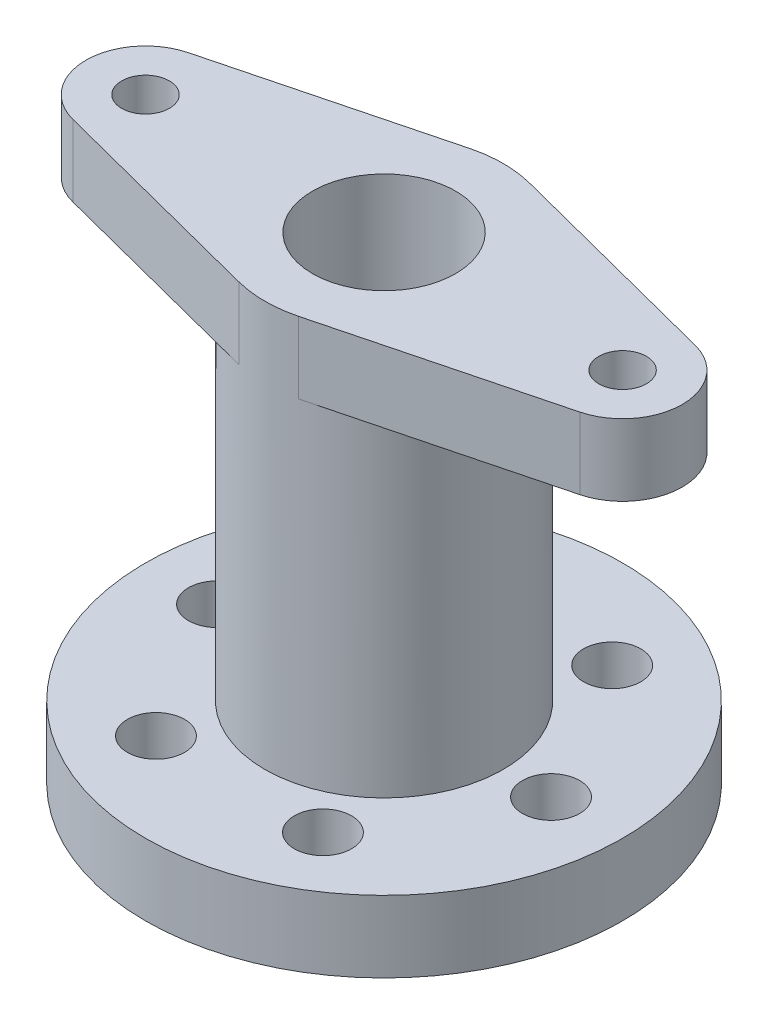
SolidWorks part; units mm, degrees
ref_plane "Front Plane" through (0, 0, 0) normal (0, 0, 1) x (1, 0, 0)
ref_plane "Top Plane" through (0, 0, 0) normal (0, 1, 0) x (1, 0, 0)
ref_plane "Right Plane" through (0, 0, 0) normal (1, 0, 0) x (0, 0, -1)
sketch "Sketch1" plane through (0, 0, 0) normal (0, 1, 0) x (1, 0, 0)
  circle A0 centre (0, 0) radius 50
  circle A1 centre (0, 0) radius 35 construction
  circle A2 centre (-35, 0) radius 6
  circle A3 centre (-17.5, 30.3109) radius 6
  circle A4 centre (17.5, 30.3109) radius 6
  circle A5 centre (35, 0) radius 6
  circle A6 centre (17.5, -30.3109) radius 6
  circle A7 centre (-17.5, -30.3109) radius 6
  point P18 (0, 0)
  dimension "D1" = 100
  dimension "D2" = 70
  dimension "D3" = 12
  dimension "D5" = 17.5
  dimension "D4" = 6
extrude "Boss-Extrude1" add sketch "Sketch1" along normal blind 15
sketch "Sketch2" plane through (0, 15, 0) normal (0, 1, 0) x (1, 0, 0)
  circle A0 centre (0, 0) radius 15
  circle A1 centre (0, 0) radius 25
  dimension "D1" = 50
  dimension "D2" = 30
extrude "Boss-Extrude2" add sketch "Sketch2" along normal blind 70
sketch "Sketch3" plane through (0, 85, 0) normal (0, 1, 0) x (1, 0, 0)
  line L0 (-53.125, 12.1031) -> (-6.25, 24.2061)
  line L6 (-53.125, -12.1031) -> (-6.25, -24.2061)
  line L8 (53.125, -12.1031) -> (6.25, -24.2061)
  line L9 (53.125, 12.1031) -> (6.25, 24.2061)
  arc A1 (-6.25, -24.2061) -> (6.25, -24.2061) centre (0, 0) ccw
  arc A2 (-53.125, 12.1031) -> (-53.125, -12.1031) centre (-50, 0) ccw
  arc A3 (53.125, -12.1031) -> (53.125, 12.1031) centre (50, 0) ccw
  arc A4 (6.25, 24.2061) -> (-6.25, 24.2061) centre (0, 0) ccw
  circle A6 centre (0, 0) radius 25 construction
  dimension "D3" = 6.25
  dimension "D1" = 25
  dimension "D2" = 12.5
extrude "Boss-Extrude3" add sketch "Sketch3" along normal blind 15
sketch "Sketch4" plane through (0, 100, 0) normal (0, 1, 0) x (1, 0, 0)
  circle A0 centre (0, 0) radius 15
  circle A1 centre (-50, 0) radius 5
  circle A2 centre (50, 0) radius 5
  dimension "D1" = 30
  dimension "D2" = 10
  dimension "D3" = 10
extrude "Cut-Extrude1" cut sketch "Sketch4" against normal blind 40
